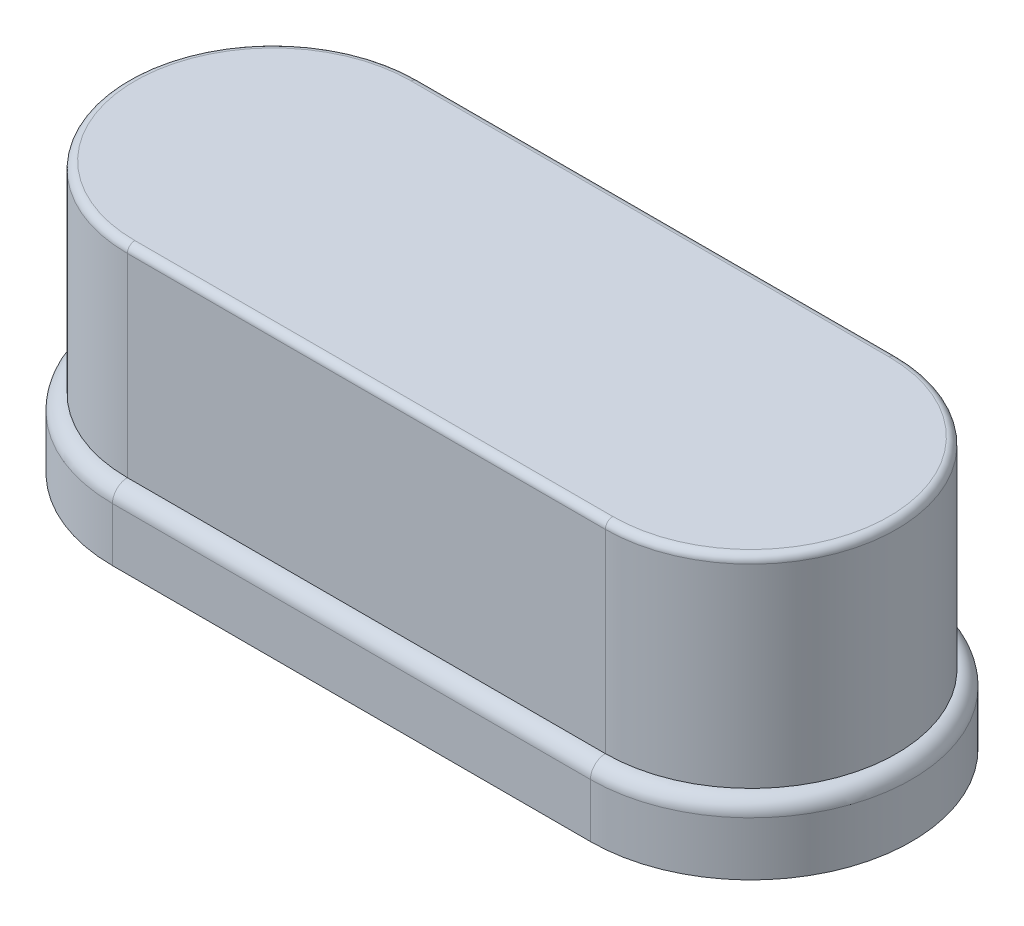
SolidWorks part; units mm, degrees
material "1060 Alloy"
ref_plane "Front Plane" through (0, 0, 0) normal (0, 0, 1) x (1, 0, 0)
ref_plane "Top Plane" through (0, 0, 0) normal (0, 1, 0) x (1, 0, 0)
ref_plane "Right Plane" through (0, 0, 0) normal (1, 0, 0) x (0, 0, -1)
sketch "Sketch2" plane through (0, 0, 0) normal (0, 1, 0) x (1, 0, 0)
  line L0 (8.7746, 14.8727) -> (8.7746, 10.5727) construction
  line L4 (8.7746, 14.8727) -> (15.1746, 14.8727)
  line L5 (11.9746, 14.8727) -> (11.9746, 12.8727) construction
  line L6 (15.1746, 14.8727) -> (15.1746, 10.5727) construction
  line L7 (8.7746, 10.5727) -> (15.1746, 10.5727)
  arc A0 (8.7746, 14.8727) -> (8.7746, 10.5727) centre (8.7746, 12.7227) ccw
  arc A1 (15.1746, 14.8727) -> (15.1746, 10.5727) centre (15.1746, 12.7227) cw
  point P0 (6.6246, 12.7227)
  point P1 (17.3246, 12.7227)
  dimension "D2" = 10.7
  dimension "D1" = 4.3
extrude "Boss-Extrude1" add sketch "Sketch2" along normal blind 0.92
fillet "Fillet3" radius 0.2 4 edges at (11.9746, 0.92, -14.8727) (17.3246, 0.92, -12.7227) (11.9746, 0.92, -10.5727) (6.6246, 0.92, -12.7227)
sketch "Sketch5" plane through (0, 0.92, 0) normal (0, 1, 0) x (1, 0, 0)
  line L0 (8.7746, 14.6727) -> (15.1746, 14.6727)
  line L1 (15.1746, 14.6727) -> (8.7746, 14.6727) construction
  line L2 (8.7746, 10.7727) -> (15.1746, 10.7727)
  line L3 (8.7746, 10.7727) -> (15.1746, 10.7727) construction
  line L4 (11.9746, 14.6727) -> (11.9746, 10.7727) construction
  arc A0 (8.7746, 10.7727) -> (8.7746, 14.6727) centre (8.7746, 12.7227) cw
  arc A1 (15.1746, 10.7727) -> (15.1746, 14.6727) centre (15.1746, 12.7227) ccw
extrude "Boss-Extrude2" add sketch "Sketch5" along normal blind 2.7
fillet "Fillet4" radius 0.1 4 edges at (11.9746, 3.62, -14.6727) (17.1246, 3.62, -12.7227) (11.9746, 3.62, -10.7727) (6.8246, 3.62, -12.7227)
